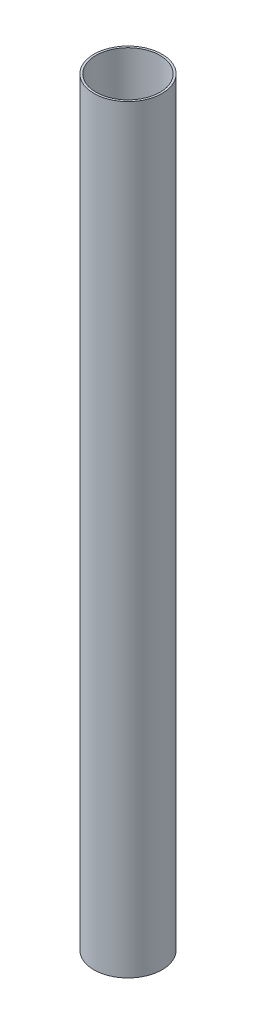
SolidWorks part; units mm, degrees
ref_plane "Front Plane" through (0, 0, 0) normal (0, 0, 1) x (1, 0, 0)
ref_plane "Top Plane" through (0, 0, 0) normal (0, 1, 0) x (1, 0, 0)
ref_plane "Right Plane" through (0, 0, 0) normal (1, 0, 0) x (0, 0, -1)
sketch "Sketch1" plane through (0, 0, 0) normal (0, 1, 0) x (1, 0, 0)
  circle A0 centre (0, 0) radius 22.225
  dimension "D1" = 44.45
extrude "Extrude-Thin1" add sketch "Sketch1" along normal blind 495.3 thin thin type one direction reverse wall 1.3462
